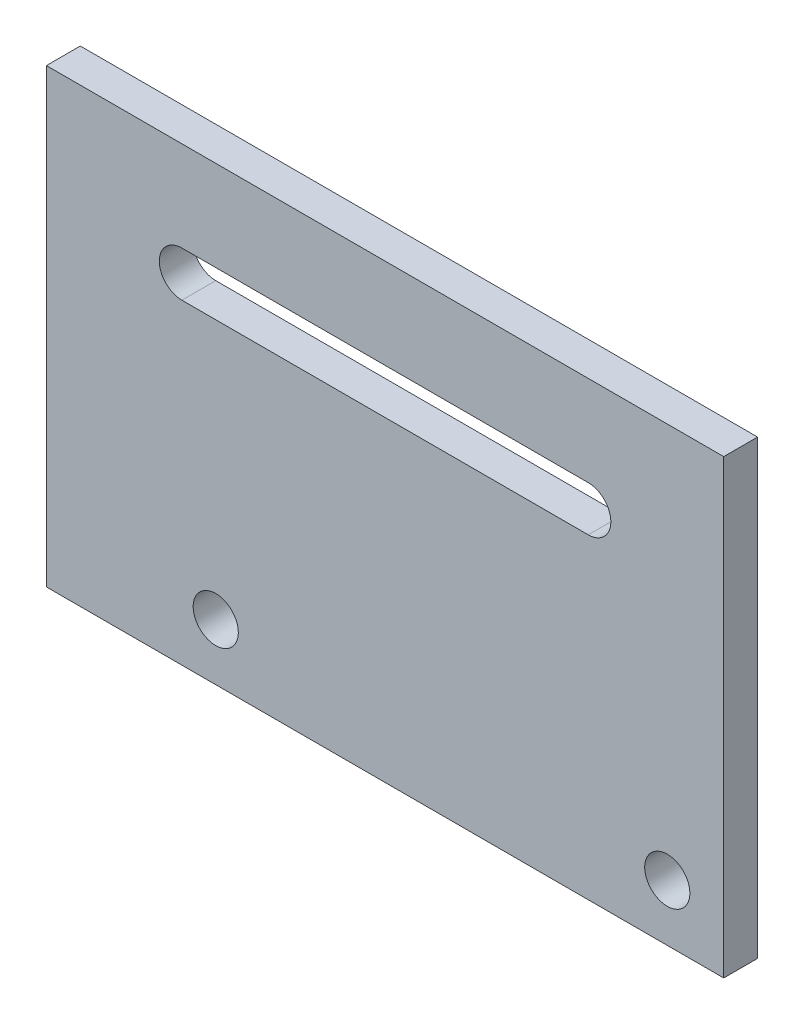
SolidWorks part; units mm, degrees
ref_plane "Front" through (0, 0, 0) normal (0, 0, 1) x (1, 0, 0)
ref_plane "Top" through (0, 0, 0) normal (0, 1, 0) x (1, 0, 0)
ref_plane "Right" through (0, 0, 0) normal (1, 0, 0) x (0, 0, -1)
sketch "Sketch4" plane through (0, 0, 0) normal (0, 0, 1) x (1, 0, 0)
  line L0 (-4.73, 5.0156) -> (15.27, 5.0156) construction
  line L1 (-12.23, 22.5156) -> (17.77, 22.5156)
  line L2 (-12.23, 22.5156) -> (-12.23, 2.5156)
  line L3 (-12.23, 2.5156) -> (17.77, 2.5156)
  line L4 (17.77, 22.5156) -> (17.77, 2.5156)
  line L6 (2.77, 17.5156) -> (2.77, 22.5156) construction
  line L7 (-6.23, 17.5156) -> (11.77, 17.5156) construction
  line L8 (-6.23, 18.5156) -> (11.77, 18.5156)
  line L9 (-6.23, 16.5156) -> (11.77, 16.5156)
  circle A1 centre (-4.73, 5.0156) radius 1
  circle A2 centre (15.27, 5.0156) radius 1
  arc A3 (-6.23, 18.5156) -> (-6.23, 16.5156) centre (-6.23, 17.5156) ccw
  arc A4 (11.77, 16.5156) -> (11.77, 18.5156) centre (11.77, 17.5156) ccw
  point P16 (2.77, 17.5156)
  dimension "D3" = 18
  dimension "D4" = 1
  dimension "D6" = 2
  dimension "D9" = 2.5
  dimension "D1" = 20
  dimension "D2" = 30
  dimension "D5" = 20
  dimension "D7" = 2.5
  dimension "D8" = 15
extrude "Boss-Extrude2" add sketch "Sketch4" along normal blind 1.5
